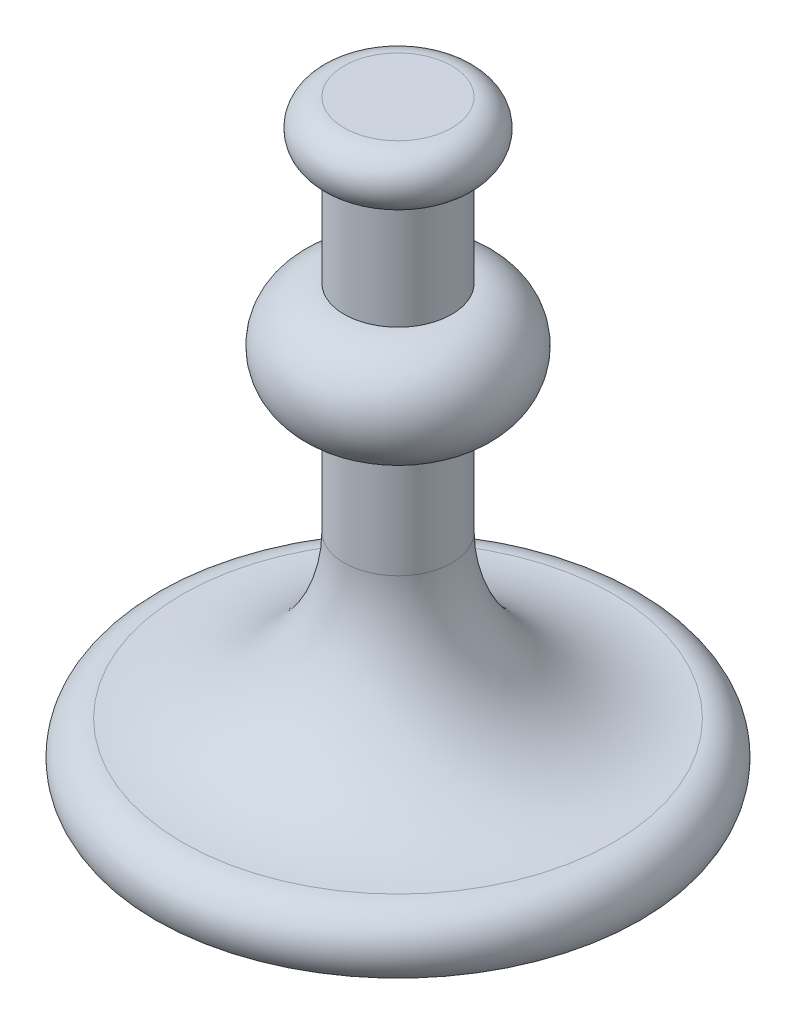
SolidWorks part; units mm, degrees
ref_plane "Front" through (0, 0, 0) normal (0, 0, 1) x (1, 0, 0)
ref_plane "Top" through (0, 0, 0) normal (0, 1, 0) x (1, 0, 0)
ref_plane "Right" through (0, 0, 0) normal (1, 0, 0) x (0, 0, -1)
sketch "Эскиз1" plane through (0, 0, 0) normal (0, 0, 1) x (1, 0, 0)
  line L0 (0, 0) -> (0, 220)
  line L1 (0, 220) -> (20, 220)
  line L2 (0, 0) -> (90, 0)
  line L3 (20, 200) -> (20, 160)
  line L4 (20, 120) -> (20, 80)
  arc A0 (20, 220) -> (20, 200) centre (20, 210) cw
  arc A1 (20, 160) -> (20, 120) centre (20, 140) cw
  arc A2 (20, 80) -> (80, 20) centre (80, 80) ccw
  arc A3 (80, 20) -> (90, 0) centre (80, 7.5) cw
  dimension "D4" = 10
  dimension "D5" = 20
  dimension "D7" = 60
  dimension "D8" = 12.5
  dimension "D1" = 220
  dimension "D2" = 20
  dimension "D3" = 90
  dimension "D6" = 40
  dimension "D9" = 80
revolve "Повернуть1" add sketch "Эскиз1" angle 360 about L0
sketch "Эскиз3" plane through (0, 0, 0) normal (1, 0, 0) x (0, 0, -1)
  line L0 (0, 10) -> (60, 10)
  line L1 (0, 227.4356) -> (0, 175.1288) construction
  line L2 (0, 126.8188) -> (0, -13.6376) construction
  line L3 (-90, 0) -> (90, 0) construction
  arc A0 (60, 10) -> (183.5921, 75) centre (60, 160) ccw
  arc A1 (183.5921, 75) -> (150.6342, 75) centre (167.1131, 86.3333) ccw
  point P10 (0, 0)
  dimension "D2" = 150
  dimension "D4" = 20
  dimension "D1" = 60
  dimension "D3" = 65
  dimension "D5" = 10
sketch "Эскиз5" plane through (0, 0, 0) normal (1, 0, 0) x (0, 0, -1)
  ellipse E0 centre (108.6342, 254.1242) end of major axis (126.1342, 254.1242) minor radius 5 construction
  dimension "D1" = 35
  dimension "D2" = 10
